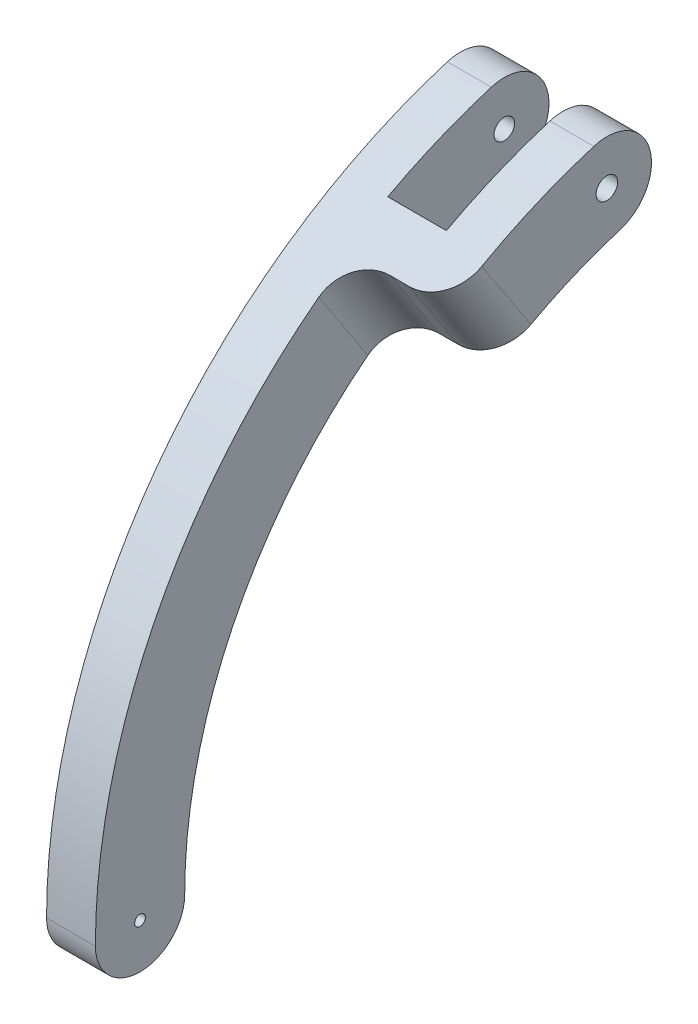
SolidWorks part; units mm, degrees
material "ABS"
ref_plane "Front Plane" through (0, 0, 0) normal (0, 0, 1) x (1, 0, 0)
ref_plane "Top Plane" through (0, 0, 0) normal (0, 1, 0) x (1, 0, 0)
ref_plane "Right Plane" through (0, 0, 0) normal (1, 0, 0) x (0, 0, -1)
sketch "Esquisse1" plane through (0, 0, 0) normal (1, 0, 0) x (0, 0, -1)
  arc A0 (-48.768, 0) -> (-14.2102, 46.6518) centre (0, 0) cw
  arc A1 (-57.912, 0) -> (-16.8746, 55.399) centre (0, 0) cw
  arc A2 (-57.912, 0) -> (-48.768, 0) centre (-53.34, 0) ccw
  arc A3 (-14.2102, 46.6518) -> (-16.8746, 55.399) centre (-15.5424, 51.0254) ccw
  circle A4 centre (-53.34, 0) radius 0.55
  circle A5 centre (-15.5424, 51.0254) radius 1.05
  dimension "D1" = 4.572
  dimension "D4" = 1.1
  dimension "D5" = 2.1
  dimension "D2" = 63.5
  dimension "D3" = 53.34
extrude "Boss.-Extru.1" add sketch "Esquisse1" along normal blind 5
sketch "Esquisse2" plane through (5, 0, 0) normal (1, 0, 0) x (0, 0, -1)
  line L0 (-31.7726, 48.418) -> (-26.7559, 40.773)
  arc A0 (-14.2102, 46.6518) -> (-48.768, 0) centre (0, 0) ccw construction
  arc A1 (-16.8746, 55.399) -> (-57.912, 0) centre (0, 0) ccw construction
  arc A2 (-14.2102, 46.6518) -> (-16.8746, 55.399) centre (-15.5424, 51.0254) ccw construction
  arc A3 (-14.2102, 46.6518) -> (-26.7559, 40.773) centre (0, 0) ccw
  arc A4 (-16.8746, 55.399) -> (-31.7726, 48.418) centre (0, 0) ccw
  arc A5 (-14.2102, 46.6518) -> (-16.8746, 55.399) centre (-15.5424, 51.0254) ccw
  dimension "D1" = 15
extrude "Boss.-Extru.2" add sketch "Esquisse2" along normal blind 10
ref_plane "Plan1" through (0, 48.418, 31.7726) normal (0, 0.8361, 0.5486) x (-1, 0, 0)
sketch "Esquisse3" plane through (0, 48.418, 31.7726) normal (0, 0.8361, 0.5486) x (-1, 0, 0)
  line L0 (0, -16.2857) -> (0, 48.418) construction
  line L1 (-4.5, -21.0693) -> (-10.5, -21.0693)
  line L2 (-4.5, -21.0693) -> (-4.5, -5)
  line L3 (-4.5, -5) -> (-10.5, -5)
  line L4 (-10.5, -21.0693) -> (-10.5, -5)
  line L6 (-15, 0) -> (-5, 0) construction
  line L9 (-15, 0) -> (-15, -16.2857) construction
  dimension "D1" = 4.5
  dimension "D2" = 4.5
  dimension "D3" = 5
extrude "Enlèv. mat.-Extru.1" cut sketch "Esquisse3" against normal through all and the other way through all
fillet "Congé1" radius 4 2 edges at (5, 44.5955, 29.2643) (15, 44.5955, 29.2643)
sketch "Esquisse4" plane through (10.5, 0, 0) normal (-1, 0, 0) x (0, 0, 1)
  circle A0 centre (15.5424, 51.0254) radius 1.1
  circle A1 centre (15.5424, 51.0254) radius 1.05 construction
  point P3 (0, 0)
  dimension "D1" = 2.2
extrude "Enlèv. mat.-Extru.2" cut sketch "Esquisse4" against normal through all
